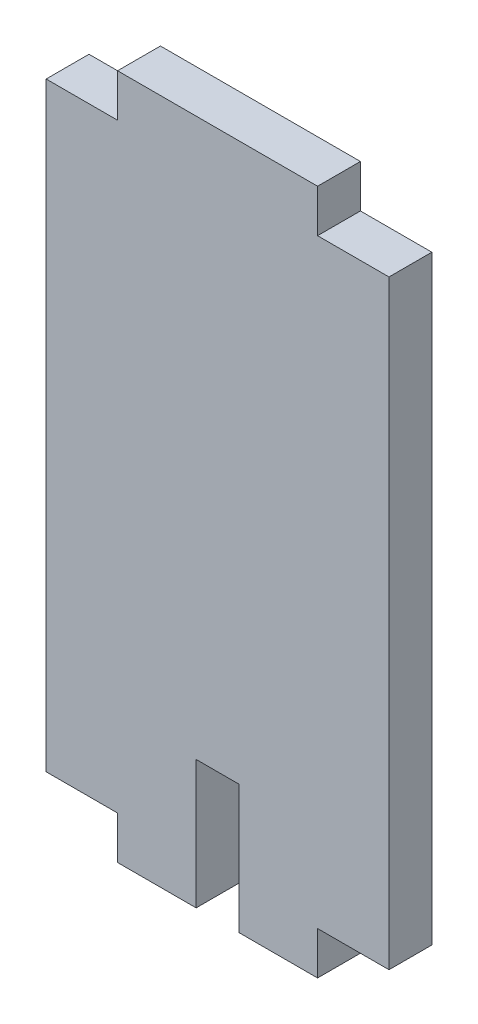
SolidWorks part; units mm, degrees
ref_plane "Front Plane" through (0, 0, 0) normal (0, 0, 1) x (1, 0, 0)
ref_plane "Top Plane" through (0, 0, 0) normal (0, 1, 0) x (1, 0, 0)
ref_plane "Right Plane" through (0, 0, 0) normal (1, 0, 0) x (0, 0, -1)
sketch "Sketch1" plane through (0, 0, 0) normal (0, 0, 1) x (1, 0, 0)
  line L1 (0, 0) -> (50.8, 0)
  line L2 (0, 0) -> (0, 101.6)
  line L3 (0, 101.6) -> (50.8, 101.6)
  line L4 (50.8, 0) -> (50.8, 101.6)
  line L5 (25.4, 101.6) -> (25.4, 0) construction
  line L6 (0, 50.8) -> (50.8, 50.8) construction
  point P120 (25.4, 50.8)
  dimension "D1" = 50.8
  dimension "D2" = 101.6
extrude "Boss-Extrude1" add sketch "Sketch1" along normal blind 6.35
sketch "Sketch2" plane through (0, 0, 6.35) normal (0, 0, 1) x (1, 0, 0)
  line L0 (25.4, 101.6) -> (25.4, 0) construction
  line L1 (50.8, 101.6) -> (0, 101.6) construction
  line L2 (0, 0) -> (50.8, 0) construction
  line L3 (50.8, 98.425) -> (40.2167, 98.425) construction
  line L4 (22.225, 0) -> (28.575, 0)
  line L5 (22.225, 0) -> (22.225, 19.05)
  line L6 (22.225, 19.05) -> (28.575, 19.05)
  line L7 (28.575, 0) -> (28.575, 19.05)
  line L8 (25.4, 19.05) -> (25.4, 0) construction
  line L9 (22.225, 9.525) -> (28.575, 9.525) construction
  line L10 (0, 101.6) -> (10.5833, 101.6)
  line L11 (0, 101.6) -> (0, 95.25)
  line L12 (0, 95.25) -> (10.5833, 95.25)
  line L13 (10.5833, 101.6) -> (10.5833, 95.25)
  line L14 (5.2917, 95.25) -> (5.2917, 101.6) construction
  line L15 (0, 98.425) -> (10.5833, 98.425) construction
  line L16 (45.5083, 95.25) -> (45.5083, 101.6) construction
  line L17 (40.2167, 101.6) -> (40.2167, 95.25)
  line L18 (50.8, 95.25) -> (40.2167, 95.25)
  line L19 (50.8, 101.6) -> (50.8, 95.25)
  line L20 (50.8, 101.6) -> (40.2167, 101.6)
  line L21 (0, 50.8) -> (50.8, 50.8) construction
  line L22 (0, 101.6) -> (0, 0) construction
  line L23 (50.8, 0) -> (50.8, 101.6) construction
  line L24 (45.5083, 6.35) -> (45.5083, 0) construction
  line L25 (50.8, 3.175) -> (40.2167, 3.175) construction
  line L26 (50.8, 0) -> (40.2167, 0)
  line L27 (50.8, 0) -> (50.8, 6.35)
  line L28 (50.8, 6.35) -> (40.2167, 6.35)
  line L29 (40.2167, 0) -> (40.2167, 6.35)
  line L30 (0, 3.175) -> (10.5833, 3.175) construction
  line L31 (5.2917, 6.35) -> (5.2917, 0) construction
  line L32 (10.5833, 0) -> (10.5833, 6.35)
  line L33 (0, 6.35) -> (10.5833, 6.35)
  line L34 (0, 0) -> (0, 6.35)
  line L35 (0, 0) -> (10.5833, 0)
  point P22 (45.5083, 98.425)
  point P37 (45.5083, 3.175)
  point P46 (5.2917, 3.175)
  point P178 (25.4, 9.525)
  point P326 (5.2917, 98.425)
  dimension "D1" = 19.05
  dimension "D2" = 6.35
  dimension "D3" = 6.35
  dimension "D4" = 10.5833
extrude "Cut-Extrude1" cut sketch "Sketch2" against normal blind 6.35
equation "\"Stock Thickness\"= .25in"
equation "\"D1@Boss-Extrude1\"=\"Stock Thickness\""
equation "\"D2@Sketch2\"=\"Stock Thickness\""
equation "\"D3@Sketch2\"=\"Stock Thickness\""
equation "\"D4@Sketch2\"=(\"D1@Sketch1\"/3)-\"Stock Thickness\""
equation "\"D1@Cut-Extrude1\"=\"Stock Thickness\""
equation "\"Joint Length\"= .75in"
equation "\"D1@Sketch2\"=\"Joint Length\""
